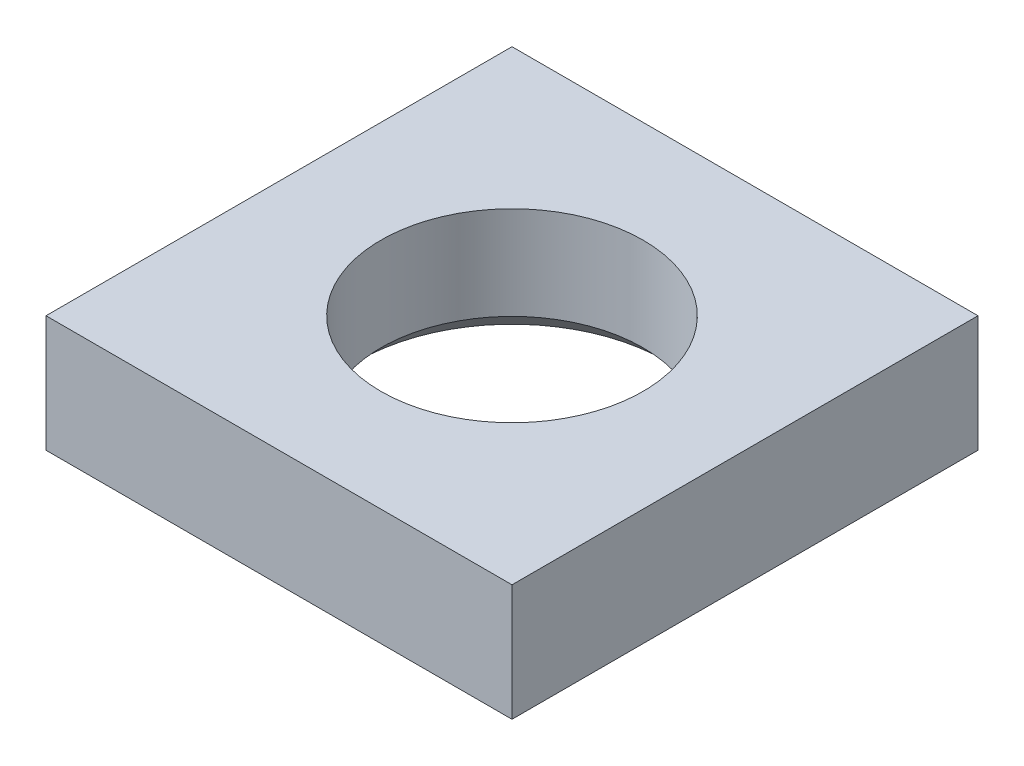
SolidWorks part; units mm, degrees
ref_plane "Front Plane" through (0, 0, 0) normal (0, 0, 1) x (1, 0, 0)
ref_plane "Top Plane" through (0, 0, 0) normal (0, 1, 0) x (1, 0, 0)
ref_plane "Right Plane" through (0, 0, 0) normal (1, 0, 0) x (0, 0, -1)
sketch "Sketch1" plane through (0, 0, 0) normal (0, 1, 0) x (1, 0, 0)
  line L1 (-25.4, -25.4) -> (25.4, -25.4)
  line L2 (-25.4, -25.4) -> (-25.4, 25.4)
  line L3 (-25.4, 25.4) -> (25.4, 25.4)
  line L4 (25.4, -25.4) -> (25.4, 25.4)
  line L5 (-25.4, -25.4) -> (25.4, 25.4) construction
  line L6 (-25.4, 25.4) -> (25.4, -25.4) construction
  point P0 (0, 0)
  dimension "D1" = 50.8
  dimension "D2" = 50.8
extrude "Boss-Extrude1" add sketch "Sketch1" along normal blind 12.7
sketch "Sketch2" plane through (0, 12.7, 0) normal (0, 1, 0) x (1, 0, 0)
  circle A0 centre (0, 0) radius 14.2875
  dimension "D1" = 28.575
extrude "Cut-Extrude1" cut sketch "Sketch2" against normal up to next
chamfer "Chamfer1" distance 2.54 angle 45 1 edges at (0, 0, -14.2875)
